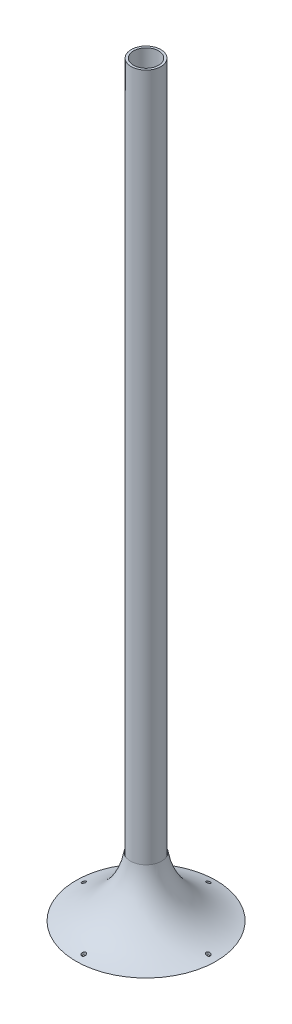
SolidWorks part; units mm, degrees
ref_plane "Front Plane" through (0, 0, 0) normal (0, 0, 1) x (1, 0, 0)
ref_plane "Top Plane" through (0, 0, 0) normal (0, 1, 0) x (1, 0, 0)
ref_plane "Right Plane" through (0, 0, 0) normal (1, 0, 0) x (0, 0, -1)
sketch "Sketch1" plane through (0, 0, 0) normal (0, 1, 0) x (1, 0, 0)
  circle A0 centre (0, 0) radius 20.447
  circle A1 centre (0, 0) radius 24.13
  dimension "D1" = 40.894
  dimension "D2" = 48.26
extrude "Boss-Extrude1" add sketch "Sketch1" along normal blind 1219.2
sketch "Sketch2" plane through (0, 0, 0) normal (0, 0, 1) x (1, 0, 0)
  line L0 (0, 0) -> (0, 1219.2) construction
  line L1 (24.13, 1219.2) -> (-24.13, 1219.2) construction
  line L2 (0, 0) -> (114.3, 0) construction
  line L3 (0, 0) -> (0, 114.3) construction
  line L4 (114.3, 0) -> (114.3, 114.3) construction
  line L5 (114.3, 114.3) -> (0, 114.3) construction
  line L6 (24.13, 0) -> (24.13, 114.3) construction
  line L7 (24.13, 0) -> (24.13, 1219.2) construction
  line L8 (24.13, 0) -> (24.13, 114.3) construction
  line L9 (24.13, 0) -> (114.3, 0)
  line L10 (25.4, 0) -> (25.4, 97.0689)
  arc A0 (114.3, 0) -> (24.13, 114.3) centre (141.6587, 114.3) cw
  dimension "D1" = 114.3
  dimension "D2" = 114.3
  dimension "D3" = 1.27
revolve "Revolve2" add sketch "Sketch2" angle 360 about L0
sketch "Sketch3" plane through (0, 0, 0) normal (0, -1, 0) x (1, 0, 0)
  line L0 (0, 0) -> (0, 114.3) construction
  circle A0 centre (0, 0) radius 114.3 construction
  circle A1 centre (0, 0) radius 101.6 construction
  circle A2 centre (0, 101.6) radius 3.2385
  circle A3 centre (0, 0) radius 101.6 construction
  circle A4 centre (101.6, 0) radius 3.2385
  circle A5 centre (0, 0) radius 101.6 construction
  circle A6 centre (0, -101.6) radius 3.2385
  circle A7 centre (0, 0) radius 101.6 construction
  circle A8 centre (-101.6, 0) radius 3.2385
  point P20 (0, 0)
  dimension "D1" = 12.7
  dimension "D2" = 6.477
  dimension "D3" = 4
extrude "Cut-Extrude1" cut sketch "Sketch3" against normal blind 1219.2
